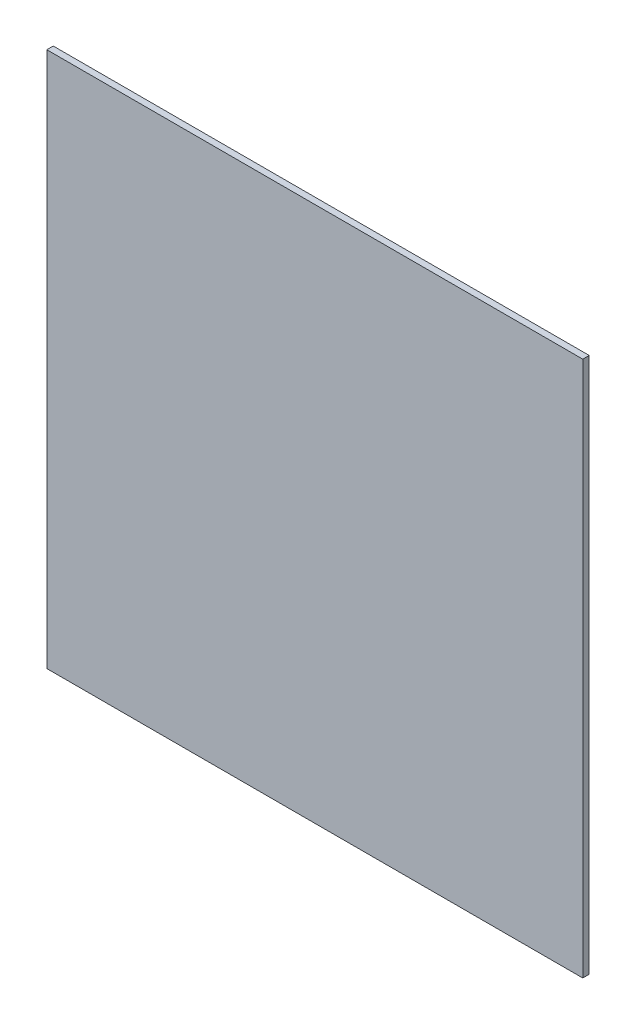
SolidWorks part; units mm, degrees
ref_plane "前视基准面" through (0, 0, 0) normal (0, 0, 1) x (1, 0, 0)
ref_plane "上视基准面" through (0, 0, 0) normal (0, 1, 0) x (1, 0, 0)
ref_plane "右视基准面" through (0, 0, 0) normal (1, 0, 0) x (0, 0, -1)
sketch "草图1" plane through (0, 0, 0) normal (0, 0, 1) x (1, 0, 0)
  line L1 (-150, 150) -> (150, 150)
  line L2 (-150, 150) -> (-150, -150)
  line L3 (-150, -150) -> (150, -150)
  line L4 (150, 150) -> (150, -150)
  line L5 (-150, 150) -> (150, -150) construction
  line L6 (-150, -150) -> (150, 150) construction
  point P0 (0, 0)
  dimension "D1" = 300
  dimension "D2" = 300
extrude "凸台-拉伸1" add sketch "草图1" along normal blind 3.6
